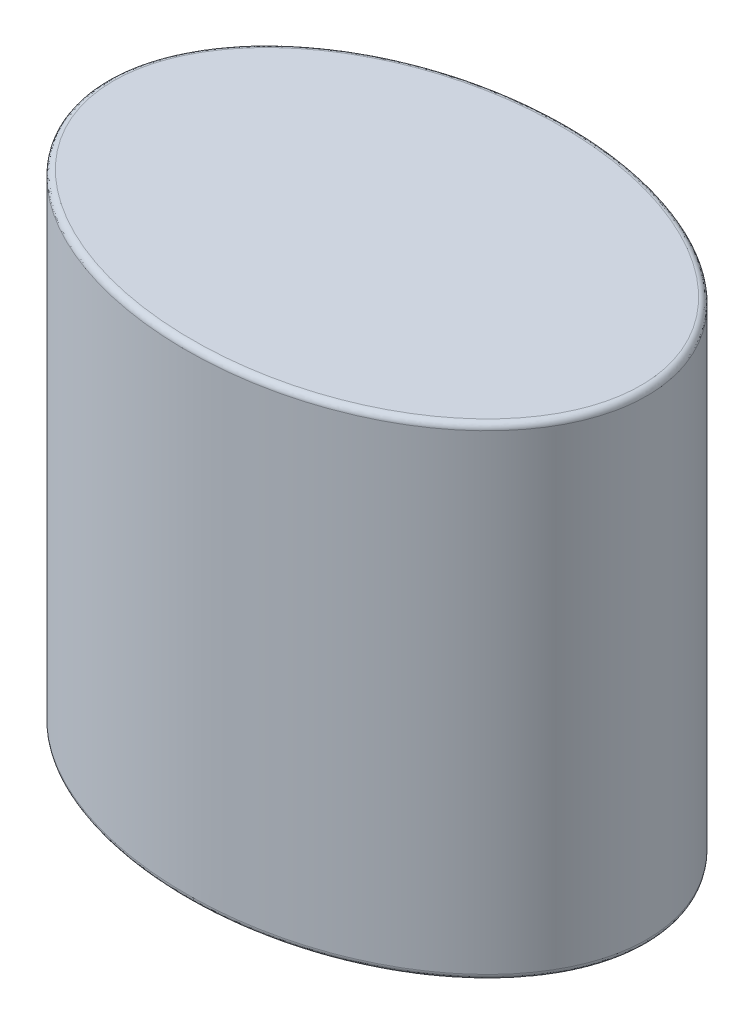
SolidWorks part; units mm, degrees
ref_plane "Front Plane" through (0, 0, 0) normal (1, 0, 0) x (0, 1, 0)
ref_plane "Top Plane" through (0, 0, 0) normal (0, 0, 1) x (0, 1, 0)
ref_plane "Right Plane" through (0, 0, 0) normal (0, 1, 0) x (-1, 0, 0)
sketch "Sketch1" plane through (0, 0, 0) normal (0, 1, 0) x (-1, 0, 0)
  spline S0 degree 3 poles (-22.3141, -1.016) (-22.3605, -0.0048) (-22.3146, 1.0063) (-22.1767, 2.0141) (-21.9467, 3.015) (-21.6253, 4.0056) (-21.2131, 4.982) (-20.7111, 5.9403) (-20.1208, 6.8766) (-19.4439, 7.7866) (-18.6828, 8.6661) (-17.8403, 9.5111) (-16.9197, 10.3174) (-15.9245, 11.0811) (-14.8591, 11.7985) (-13.7278, 12.466) (-12.5356, 13.0803) (-11.2876, 13.6383) (-9.9893, 14.1374) (-8.6465, 14.575) (-7.2652, 14.9491) (-5.8514, 15.2577) (-4.4114, 15.4994) (-2.9518, 15.673) (-1.4789, 15.7777) (0.0005, 15.8129) (1.48, 15.7785) (2.953, 15.6746) (4.4127, 15.5018) (5.8528, 15.2609) (7.2667, 14.953) (8.6483, 14.5797) (9.9913, 14.1428) (11.2899, 13.6445) (12.5382, 13.0871) (13.7307, 12.4735) (14.8624, 11.8066) (15.9282, 11.0898) (16.9238, 10.3266) (17.8449, 9.5208) (18.6878, 8.6763) (19.4494, 7.7972) (20.1267, 6.8875) (20.7176, 5.9516) (21.2201, 4.9936) (21.6329, 4.0174) (21.9548, 3.027) (22.1853, 2.0262) (22.3238, 1.0185) (22.3702, 0.0074) (22.3244, -1.0038) (22.1864, -2.0116) (21.9565, -3.0125) (21.6351, -4.0031) (21.2229, -4.9795) (20.7209, -5.9378) (20.1305, -6.8741) (19.4536, -7.784) (18.6925, -8.6636) (17.85, -9.5086) (16.9294, -10.3149) (15.9343, -11.0786) (14.8688, -11.796) (13.7375, -12.4635) (12.5453, -13.0778) (11.2973, -13.6358) (9.9991, -14.1349) (8.6563, -14.5725) (7.2749, -14.9466) (5.8611, -15.2552) (4.4212, -15.4969) (2.9615, -15.6705) (1.4887, -15.7751) (0.0092, -15.8104) (-1.4703, -15.776) (-2.9432, -15.6721) (-4.403, -15.4993) (-5.8431, -15.2584) (-7.257, -14.9505) (-8.6386, -14.5772) (-9.9816, -14.1403) (-11.2801, -13.642) (-12.5284, -13.0846) (-13.721, -12.471) (-14.8526, -11.8041) (-15.9185, -11.0873) (-16.914, -10.3241) (-17.8351, -9.5183) (-18.6781, -8.6738) (-19.4397, -7.7947) (-20.117, -6.885) (-20.7079, -5.9491) (-21.2104, -4.9911) (-21.6232, -4.0149) (-21.9451, -3.0245) (-22.1756, -2.0237) (-22.3141, -1.016) (-22.3605, -0.0048) (-22.3146, 1.0063) knots -0.025254 -0.016767 -0.008362 0 0.008362 0.016767 0.025254 0.033862 0.042624 0.051572 0.060728 0.070113 0.07974 0.089619 0.099754 0.110144 0.120784 0.131667 0.14278 0.15411 0.165637 0.177343 0.189205 0.201201 0.213305 0.22549 0.237731 0.25 0.262269 0.27451 0.286695 0.298799 0.310795 0.322657 0.334363 0.34589 0.35722 0.368333 0.379216 0.389856 0.400246 0.410381 0.42026 0.429887 0.439272 0.448428 0.457376 0.466138 0.474746 0.483233 0.491638 0.5 0.508362 0.516767 0.525254 0.533862 0.542624 0.551572 0.560728 0.570113 0.57974 0.589619 0.599754 0.610144 0.620784 0.631667 0.64278 0.65411 0.665637 0.677343 0.689205 0.701201 0.713305 0.72549 0.737731 0.75 0.762269 0.77451 0.786695 0.798799 0.810795 0.822657 0.834363 0.84589 0.85722 0.868333 0.879216 0.889856 0.900246 0.910381 0.92026 0.929887 0.939272 0.948428 0.957376 0.966138 0.974746 0.983233 0.991638 1 1.008362 1.016767 1.025254 only from (-22.3451, -0.0048) to (-22.3451, -0.0048)
extrude "Boss-Extrude1" add sketch "Sketch1" along normal blind 40
fillet "Fillet1" radius 0.5 2 edges
